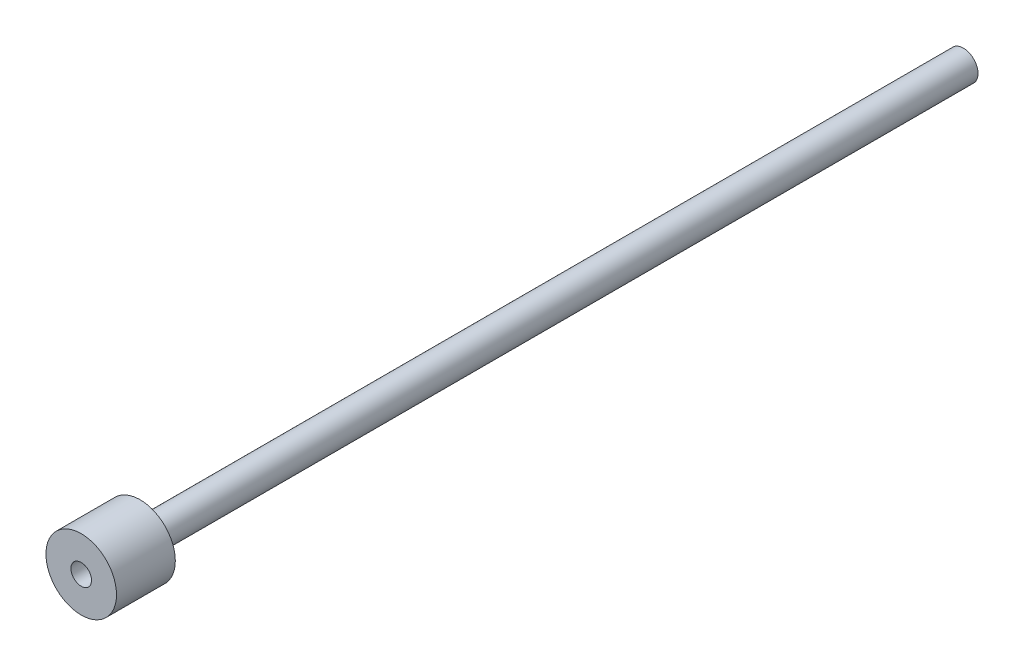
SolidWorks part; units mm, degrees
ref_plane "Front Plane" through (0, 0, 0) normal (0, 0, 1) x (1, 0, 0)
ref_plane "Top Plane" through (0, 0, 0) normal (0, 1, 0) x (1, 0, 0)
ref_plane "Right Plane" through (0, 0, 0) normal (1, 0, 0) x (0, 0, -1)
sketch "Sketch1" plane through (0, 0, 0) normal (0, 0, 1) x (1, 0, 0)
  circle A0 centre (0, 0) radius 12
  dimension "D1" = 24
extrude "Boss-Extrude1" add sketch "Sketch1" along normal blind 20
sketch "Sketch2" plane through (0, 0, 0) normal (0, 0, -1) x (-1, 0, 0)
  circle A0 centre (0, 0) radius 8.75
  circle A1 centre (0, 0) radius 5
  dimension "D1" = 17.5
  dimension "D2" = 10
extrude "Cut-Extrude1" cut sketch "Sketch2" against normal blind 15
sketch "Sketch3" plane through (0, 0, 20) normal (0, 0, 1) x (1, 0, 0)
  circle A0 centre (0, 0) radius 3.5
  dimension "D1" = 7
extrude "Cut-Extrude2" cut sketch "Sketch3" against normal through all
sketch "Sketch4" plane through (0, 0, 0) normal (0, 0, -1) x (-1, 0, 0)
  circle A0 centre (0, 0) radius 3.5 construction
  circle A1 centre (0, 0) radius 5
  circle A3 centre (0, 0) radius 3.5
  circle A12 centre (0, 0) radius 5
  dimension "D1" = 0
extrude "Boss-Extrude2" add sketch "Sketch4" along normal blind 280
